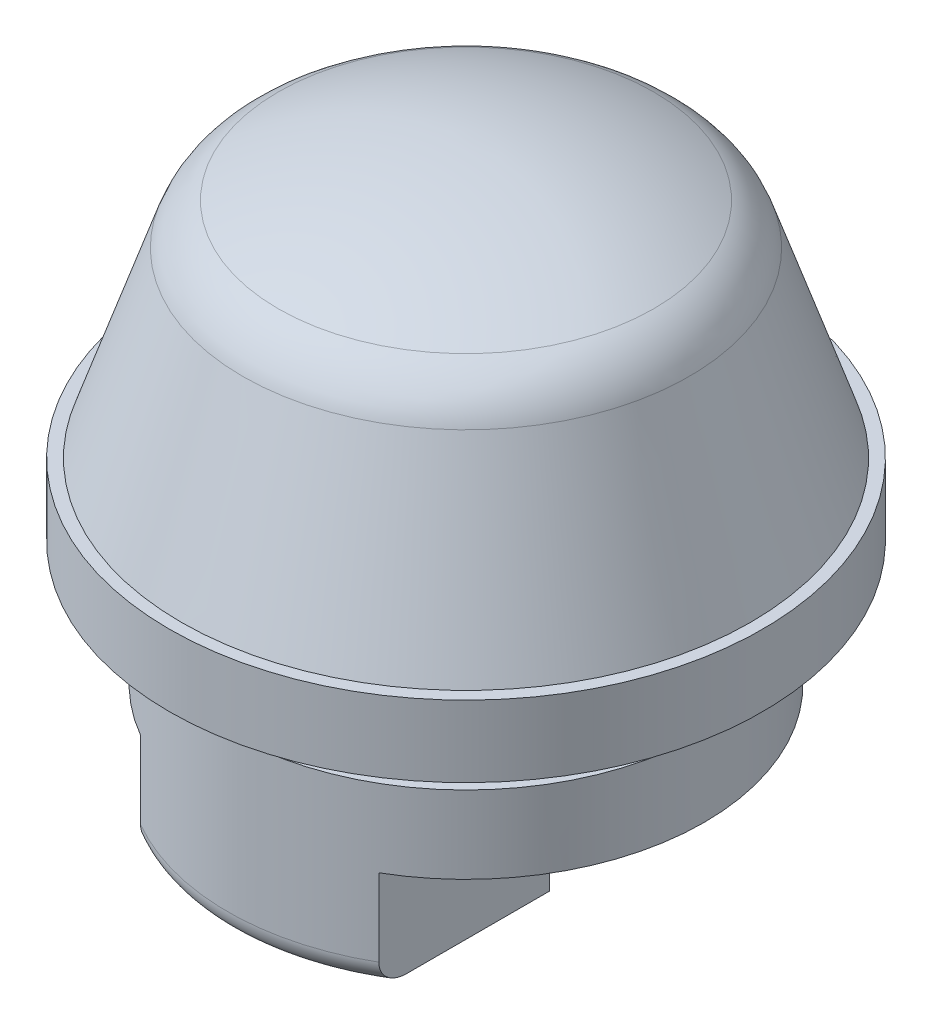
SolidWorks part; units mm, degrees
ref_plane "Front" through (0, 0, 0) normal (0, 0, 1) x (1, 0, 0)
ref_plane "Top" through (0, 0, 0) normal (0, 1, 0) x (1, 0, 0)
ref_plane "Right" through (0, 0, 0) normal (1, 0, 0) x (0, 0, -1)
sketch "Sketch1" plane through (0, 0, 0) normal (0, 0, 1) x (1, 0, 0)
  line L0 (0, 0) -> (0, 28.5)
  line L1 (-18, 23.5) -> (-23.9, 6)
  line L2 (-23.9, 6) -> (-24.9, 6)
  line L3 (-24.9, 6) -> (-24.9, 0)
  line L4 (-24.9, 0) -> (0, 0)
  arc A0 (0, 28.5) -> (-18, 23.5) centre (0, -6.4) ccw
  dimension "D1" = 6
  dimension "D2" = 28.5
  dimension "D3" = 23.9
  dimension "D4" = 18
  dimension "D5" = 1
  dimension "D6" = 5
revolve "Revolve1" add sketch "Sketch1" angle 360 about L0
fillet "Fillet1" radius 6 1 edges at (0, 23.5, -18)
sketch "Sketch2" plane through (0, 0, 0) normal (0, -1, 0) x (1, 0, 0)
  circle A0 centre (0, 0) radius 9
  dimension "D1" = 18
extrude "Boss-Extrude1" add sketch "Sketch2" along normal blind 4
sketch "Sketch6" plane through (0, -4, 0) normal (0, -1, 0) x (1, 0, 0)
  circle A0 centre (0, 0) radius 20
  dimension "D1" = 40
extrude "Boss-Extrude2" add sketch "Sketch6" along normal blind 15
sketch "Sketch7" plane through (0, -19, 0) normal (0, -1, 0) x (1, 0, 0)
  line L1 (-10, 17.3205) -> (-42.0334, 17.3205)
  line L2 (-10, 17.3205) -> (-10, -17.3205)
  line L3 (-10, -17.3205) -> (-42.0334, -17.3205)
  line L4 (-42.0334, 17.3205) -> (-42.0334, -17.3205)
  line L5 (10, 17.3205) -> (39.3677, 17.3205)
  line L6 (10, 17.3205) -> (10, -17.3205)
  line L7 (10, -17.3205) -> (39.3677, -17.3205)
  line L8 (39.3677, 17.3205) -> (39.3677, -17.3205)
  circle A0 centre (0, 0) radius 20 construction
  dimension "D1" = 20
extrude "Cut-Extrude1" cut sketch "Sketch7" against normal blind 8.5
sketch "Sketch9" plane through (0, -19, 0) normal (0, -1, 0) x (1, 0, 0)
  line L5 (-4.7286, 3) -> (-27.5, 3)
  line L6 (27.5, 3) -> (4.7286, 3)
  line L8 (27.5, 3) -> (27.5, -3)
  line L9 (27.5, -3) -> (4.7286, -3)
  line L10 (-27.5, 3) -> (-27.5, -3)
  line L11 (27.5, 3) -> (-27.5, -3) construction
  line L12 (27.5, -3) -> (-27.5, 3) construction
  line L13 (-4.7286, -3) -> (-27.5, -3)
  arc A2 (4.7286, 3) -> (-4.7286, 3) centre (0, 0) ccw
  arc A3 (-4.7286, -3) -> (4.7286, -3) centre (0, 0) ccw
  dimension "D1" = 5.6
  dimension "D2" = 55
  dimension "D3" = 6
extrude "Cut-Extrude2" cut sketch "Sketch9" against normal blind 8.5
sketch "Sketch10" plane through (0, -19, 0) normal (0, -1, 0) x (1, 0, 0)
  circle A0 centre (0, 0) radius 7.1
  dimension "D1" = 14.2
extrude "Cut-Extrude3" cut sketch "Sketch10" against normal blind 3
fillet "Fillet2" radius 2 2 edges at (0, -19, -20) (0, -19, 20)
